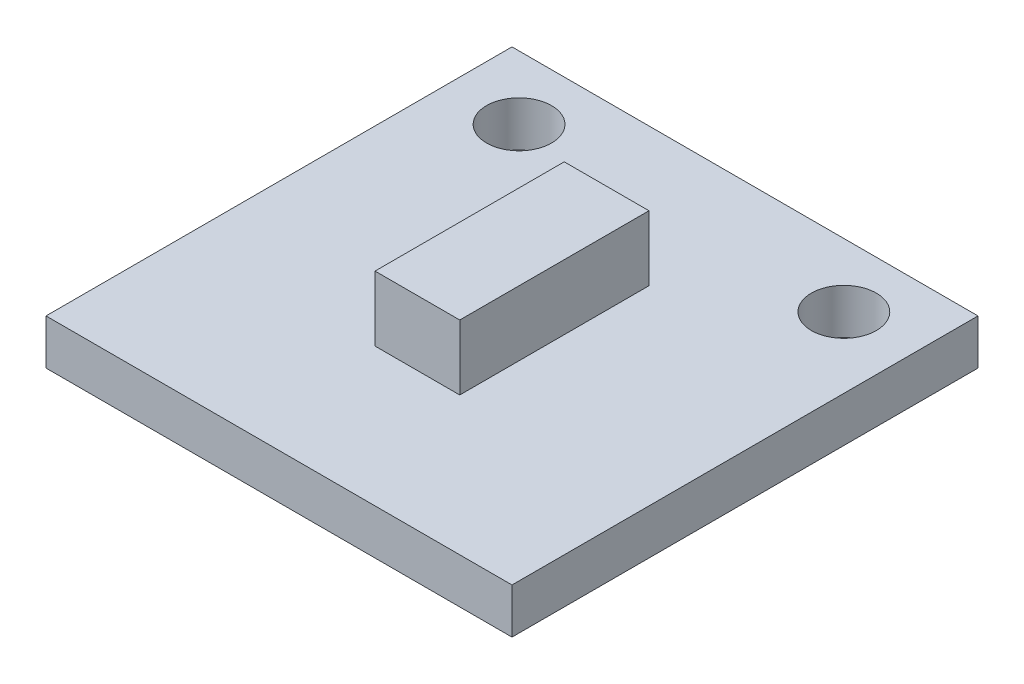
SolidWorks part; units mm, degrees
ref_plane "Front Plane" through (0, 0, 0) normal (0, 0, 1) x (1, 0, 0)
ref_plane "Top Plane" through (0, 0, 0) normal (0, 1, 0) x (1, 0, 0)
ref_plane "Right Plane" through (0, 0, 0) normal (1, 0, 0) x (0, 0, -1)
sketch "Sketch1" plane through (0, 0, 0) normal (0, 1, 0) x (1, 0, 0)
  line L1 (-8.25, -8.25) -> (8.25, -8.25)
  line L2 (-8.25, -8.25) -> (-8.25, 8.25)
  line L3 (-8.25, 8.25) -> (8.25, 8.25)
  line L4 (8.25, -8.25) -> (8.25, 8.25)
  line L5 (-8.25, -8.25) -> (8.25, 8.25) construction
  line L6 (-8.25, 8.25) -> (8.25, -8.25) construction
  line L7 (-5.75, -6) -> (5.75, -6) construction
  line L8 (-5.75, -6) -> (-5.75, 6) construction
  line L9 (-5.75, 6) -> (5.75, 6) construction
  line L10 (5.75, -6) -> (5.75, 6) construction
  line L11 (-5.75, -6) -> (5.75, 6) construction
  line L12 (-5.75, 6) -> (5.75, -6) construction
  circle A0 centre (-5.75, 6) radius 1.15
  circle A1 centre (5.75, 6) radius 1.15
  point P0 (0, 0)
  point P5 (0, 0)
  dimension "D1" = 2.3
  dimension "D2" = 11.5
  dimension "D3" = 16.5
  dimension "D4" = 1.1
extrude "Boss-Extrude1" add sketch "Sketch1" along normal blind 1.6
sketch "Sketch2" plane through (0, 1.6, 0) normal (0, 1, 0) x (1, 0, 0)
  line L1 (-1.5, -3.35) -> (1.5, -3.35)
  line L2 (-1.5, -3.35) -> (-1.5, 3.35)
  line L3 (-1.5, 3.35) -> (1.5, 3.35)
  line L4 (1.5, -3.35) -> (1.5, 3.35)
  line L5 (-1.5, -3.35) -> (1.5, 3.35) construction
  line L6 (-1.5, 3.35) -> (1.5, -3.35) construction
  point P0 (0, 0)
  dimension "D1" = 3
  dimension "D2" = 6.7
extrude "Boss-Extrude2" add sketch "Sketch2" along normal blind 2.3
